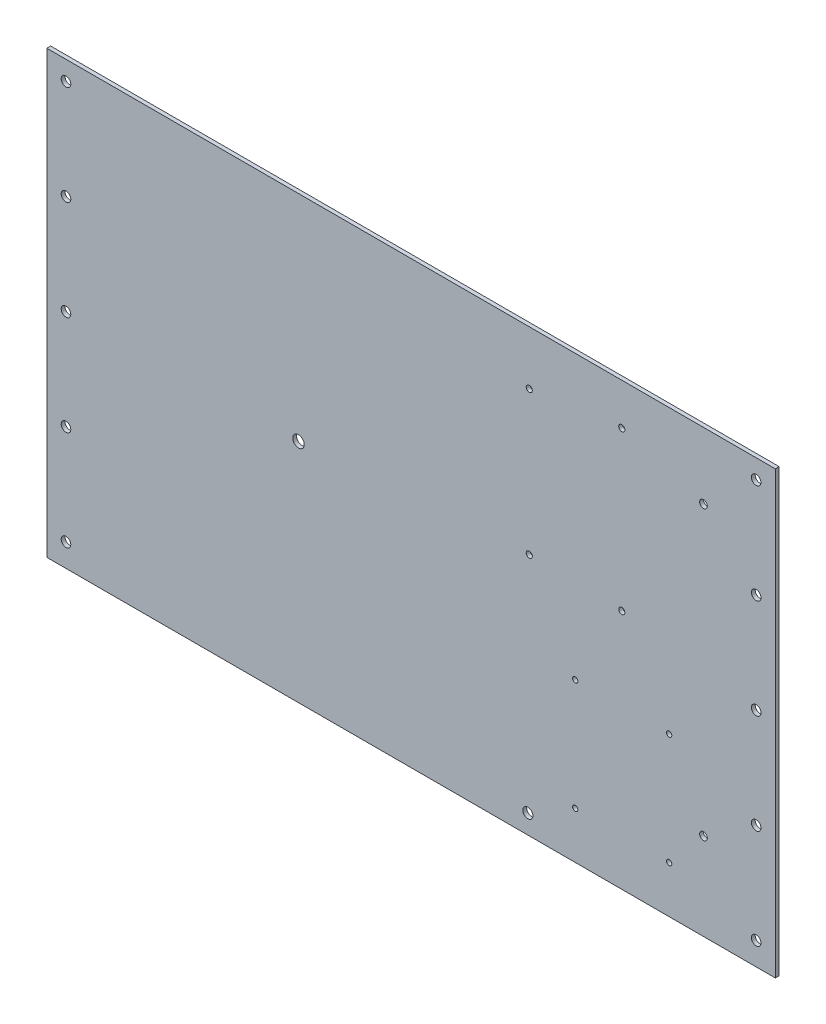
SolidWorks part; units mm, degrees
material "3.1645 (EN-AW 2030)"
ref_plane "Přední rovina" through (0, 0, 0) normal (0, 0, 1) x (1, 0, 0)
ref_plane "Horní rovina" through (0, 0, 0) normal (0, 1, 0) x (1, 0, 0)
ref_plane "Pravá rovina" through (0, 0, 0) normal (1, 0, 0) x (0, 0, -1)
sketch "Skica2" plane through (0, 0, 0) normal (0, 0, 1) x (1, 0, 0)
  line L0 (-4.5243, -350) -> (-4.5243, 0) construction
  line L1 (-4.5243, -80) -> (-384.5243, -80)
  line L2 (-4.5243, -80) -> (-4.5243, -310)
  line L3 (-4.5243, -310) -> (-384.5243, -310)
  line L4 (-384.5243, -80) -> (-384.5243, -310)
  line L5 (-384.5243, -350) -> (-384.5243, 0) construction
  dimension "D1" = 380
  dimension "D2" = 230
extrude "Přidat vysunutím1" add sketch "Skica2" along normal blind 2
sketch "Skica3" plane through (0, 0, 2) normal (0, 0, 1) x (1, 0, 0)
  line L0 (-384.5243, -80) -> (-384.5243, -310) construction
  line L1 (-4.5243, -80) -> (-384.5243, -80) construction
  circle A0 centre (-374.5243, -90) radius 2.5
  circle A1 centre (-14.5243, -90) radius 2.5
  circle A2 centre (-14.5243, -142) radius 2.5
  circle A3 centre (-14.5243, -194) radius 2.5
  circle A4 centre (-14.5243, -246) radius 2.5
  circle A5 centre (-14.5243, -298) radius 2.5
  circle A6 centre (-374.5243, -142) radius 2.5
  circle A7 centre (-374.5243, -194) radius 2.5
  circle A8 centre (-374.5243, -246) radius 2.5
  circle A9 centre (-374.5243, -298) radius 2.5
  dimension "D1" = 5
  dimension "D2" = 10
  dimension "D3" = 10
  dimension "D4" = 2
  dimension "D5" = 5
extrude "Odebrat vysunutím1" cut sketch "Skica3" against normal blind 2 contours A0 | A6 | A7 | A8 | A9 | A4 | A5 | A3 | A2 | A1
sketch "Skica4" plane through (0, 0, 2) normal (0, 0, 1) x (1, 0, 0)
  circle A0 centre (-84.6191, -101.6675) radius 1.6048
  circle A1 centre (-132.8791, -108.0175) radius 1.5897
  circle A2 centre (-132.8791, -182.9475) radius 1.5875
  circle A3 centre (-84.6191, -184.2175) radius 1.5875
  circle A4 centre (-108.9089, -227.5184) radius 1.375
  circle A5 centre (-59.9089, -227.5184) radius 1.375
  circle A6 centre (-59.9089, -285.5184) radius 1.3725
  circle A7 centre (-108.9089, -285.5184) radius 1.3622
  circle A8 centre (-42.0243, -264.6373) radius 2
  circle A9 centre (-42.0243, -114.6373) radius 1.9951
  circle A10 centre (-253.2508, -191.9509) radius 3
  dimension "D1" = 6
extrude "Odebrat vysunutím2" cut sketch "Skica4" against normal blind 2
sketch "Skica5" plane through (0, 0, 2) normal (0, 0, 1) x (1, 0, 0)
  line L0 (-136.7243, -300) -> (-133.6142, -300) construction
  circle A0 centre (-133.6142, -300) radius 2.6
  dimension "D1" = 5.2
extrude "Odebrat vysunutím3" cut sketch "Skica5" against normal blind 2
